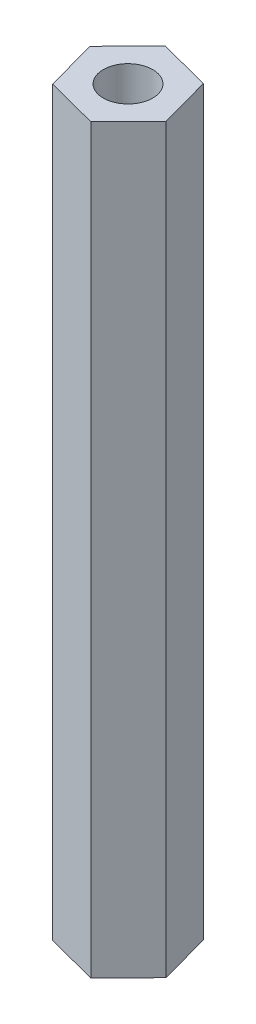
SolidWorks part; units mm, degrees
ref_plane "前视基准面" through (0, 0, 0) normal (0, 0, 1) x (1, 0, 0)
ref_plane "上视基准面" through (0, 0, 0) normal (0, 1, 0) x (1, 0, 0)
ref_plane "右视基准面" through (0, 0, 0) normal (1, 0, 0) x (0, 0, -1)
sketch "草图1" plane through (0, 0, 0) normal (0, 1, 0) x (1, 0, 0)
  line L1 (0.8581, -3.1172) -> (3.1286, -0.8155)
  line L2 (3.1286, -0.8155) -> (2.2705, 2.3017)
  line L3 (2.2705, 2.3017) -> (-0.8581, 3.1172)
  line L4 (-0.8581, 3.1172) -> (-3.1286, 0.8155)
  line L5 (-3.1286, 0.8155) -> (-2.2705, -2.3017)
  line L6 (-2.2705, -2.3017) -> (0.8581, -3.1172)
  circle A0 centre (0, 0) radius 2.8 construction
  circle A1 centre (0, 0) radius 1.5
  dimension "D2" = 3
  dimension "D1" = 5.6
extrude "凸台-拉伸1" add sketch "草图1" along normal blind 45
